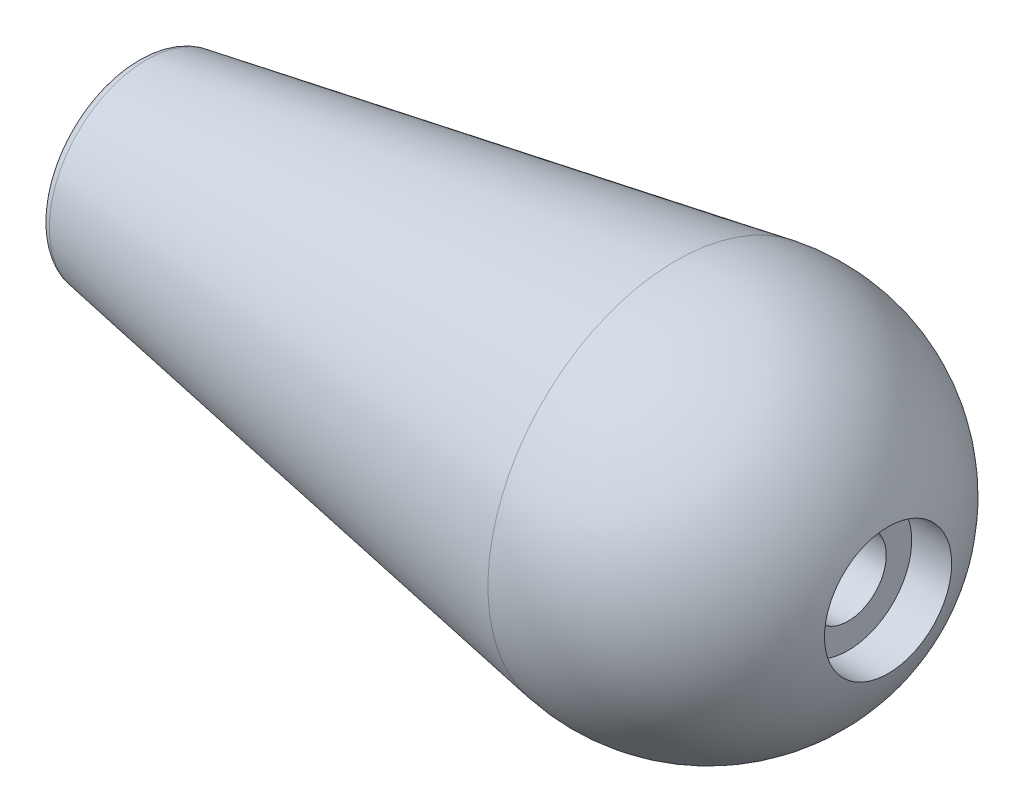
SolidWorks part; units mm, degrees
ref_plane "Front Plane" through (0, 0, 0) normal (0, 0, 1) x (1, 0, 0)
ref_plane "Top Plane" through (0, 0, 0) normal (0, 1, 0) x (1, 0, 0)
ref_plane "Right Plane" through (0, 0, 0) normal (1, 0, 0) x (0, 0, -1)
sketch "Sketch1" plane through (0, 0, 0) normal (0, 1, 0) x (1, 0, 0)
  line L0 (0, 0) -> (120, 0)
  line L1 (0, 0) -> (0, 15)
  line L2 (0, 15) -> (84.928, 29.5681)
  arc A0 (120, 0) -> (84.928, 29.5681) centre (90, 0) ccw
  dimension "D2" = 30
  dimension "D1" = 120
  dimension "D3" = 15
revolve "Revolve2" add sketch "Sketch1" angle 360 about L0
sketch "Sketch5" plane through (0, 0, 0) normal (0, 0, 1) x (1, 0, 0)
  line L0 (0, 0) -> (0, 10)
  line L1 (0, 15) -> (0, -15) construction
  line L2 (0, 10) -> (8, 10)
  line L3 (8, 10) -> (8, 6)
  line L4 (8, 6) -> (112, 6)
  line L5 (112, 6) -> (112, 10)
  line L6 (112, 10) -> (120, 10)
  line L7 (120, 10) -> (120, 0)
  line L8 (120, 0) -> (0, 0)
  arc A0 (84.928, -29.5681) -> (84.928, 29.5681) centre (90, 0) ccw construction
  dimension "D1" = 10
  dimension "D2" = 8
  dimension "D3" = 8
  dimension "D4" = 6
revolve "Cut-Revolve1" cut sketch "Sketch5" angle 360 about L8
fillet "Fillet1" radius 2 1 edges at (0, 0, 15)
